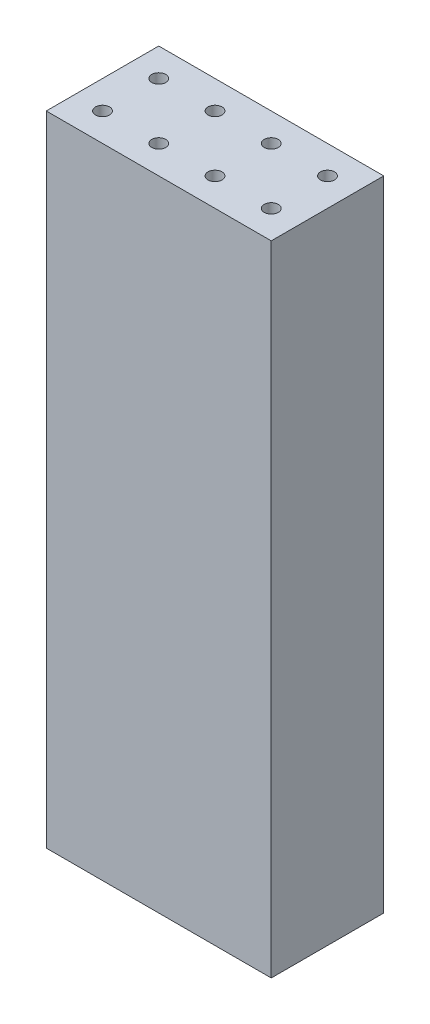
SolidWorks part; units mm, degrees
ref_plane "Front Plane" through (0, 0, 0) normal (0, 0, 1) x (1, 0, 0)
ref_plane "Top Plane" through (0, 0, 0) normal (0, 1, 0) x (1, 0, 0)
ref_plane "Right Plane" through (0, 0, 0) normal (1, 0, 0) x (0, 0, -1)
sketch "Sketch1" plane through (0, 0, 0) normal (0, 1, 0) x (1, 0, 0)
  line L0 (-50.8, -25.4) -> (50.8, 25.4) construction
  line L1 (-50.8, 25.4) -> (50.8, 25.4)
  line L2 (-50.8, 25.4) -> (-50.8, -25.4)
  line L3 (-50.8, -25.4) -> (50.8, -25.4)
  line L4 (50.8, 25.4) -> (50.8, -25.4)
  dimension "D1" = 101.6
  dimension "D2" = 50.8
extrude "Boss-Extrude1" add sketch "Sketch1" along normal blind 288.29
sketch "Sketch3" plane through (0, 288.29, 0) normal (0, 1, 0) x (1, 0, 0)
  line L0 (-50.8, 25.4) -> (-50.8, -25.4) construction
  line L1 (50.8, 25.4) -> (-50.8, 25.4) construction
  circle A0 centre (-38.1, 12.7) radius 3.175
  dimension "D1" = 6.35
  dimension "D2" = 12.7
  dimension "D3" = 12.7
extrude "Cut-Extrude1" cut sketch "Sketch3" against normal blind 10
pattern_linear "LPattern1" count 4 spacing 25.4 along (1, 0, 0) count 2 spacing 25.4 along (0, 0, 1) of "Cut-Extrude1"
